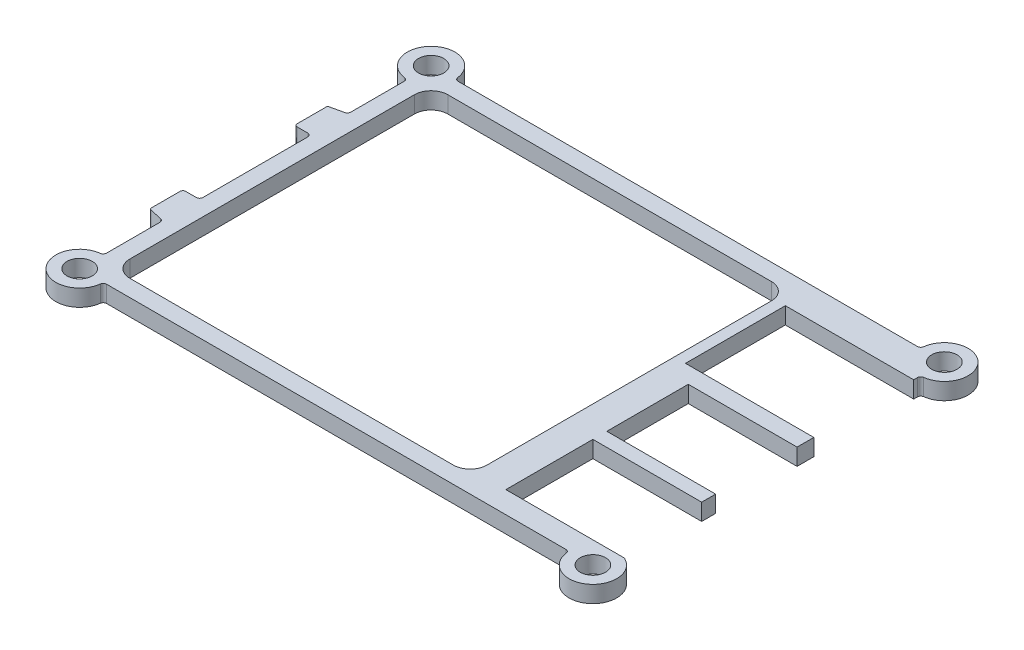
SolidWorks part; units mm, degrees
material "Balsa"
ref_plane "Front Plane" through (0, 0, 0) normal (0, 0, 1) x (1, 0, 0)
ref_plane "Top Plane" through (0, 0, 0) normal (0, 1, 0) x (1, 0, 0)
ref_plane "Right Plane" through (0, 0, 0) normal (1, 0, 0) x (0, 0, -1)
sketch "Sketch1" plane through (0, 0, 0) normal (0, 1, 0) x (1, 0, 0)
  line L0 (46, 0) -> (46, -63) construction
  line L5 (4.265, 0) -> (87.735, 0)
  line L6 (3.2, -3.25) -> (88.8, -3.25) construction
  line L7 (3.2, -3.25) -> (3.2, -59.75) construction
  line L8 (3.2, -59.75) -> (88.8, -59.75) construction
  line L9 (88.8, -3.25) -> (88.8, -59.75) construction
  line L10 (3.2, -3.25) -> (88.8, -59.75) construction
  line L11 (3.2, -59.75) -> (88.8, -3.25) construction
  line L12 (0, -4.265) -> (0, -58.735)
  line L14 (92, -4.265) -> (92, -58.735)
  line L15 (4.265, -63) -> (87.735, -63)
  circle A0 centre (0, 0) radius 2.265
  circle A1 centre (92, 0) radius 2.265
  circle A2 centre (92, -63) radius 2.265
  circle A3 centre (0, -63) radius 2.265
  arc A4 (4.265, 0) -> (0, -4.265) centre (0, 0) ccw
  arc A5 (92, -4.265) -> (87.735, 0) centre (92, 0) ccw
  arc A6 (87.735, -63) -> (92, -58.735) centre (92, -63) ccw
  arc A7 (0, -58.735) -> (4.265, -63) centre (0, -63) ccw
  point P7 (46, -31.5)
  dimension "D5" = 4.53
  dimension "D6" = 2
  dimension "D1" = 92
  dimension "D2" = 63
  dimension "D3" = 85.6
  dimension "D4" = 56.5
extrude "Boss-Extrude1" add sketch "Sketch1" along normal blind 3
sketch "Sketch2" plane through (0, 3, 0) normal (0, 1, 0) x (1, 0, 0)
  line L0 (0, -31.5) -> (92, -31.5) construction
  line L1 (0, -4.265) -> (0, -58.735) construction
  line L2 (92, -58.735) -> (92, -4.265) construction
  line L4 (0, -21.5) -> (6.5, -21.5)
  line L5 (0, -21.5) -> (0, -41.5)
  line L6 (0, -41.5) -> (6.5, -41.5)
  line L7 (6.5, -21.5) -> (6.5, -41.5)
  point P11 (0, -31.5)
  dimension "D1" = 20
  dimension "D2" = 6.5
extrude "Cut-Extrude1" cut sketch "Sketch2" against normal blind 3
sketch "Sketch3" plane through (0, 3, 0) normal (0, 1, 0) x (1, 0, 0)
  line L0 (-2.7, -15.5) -> (0, -14.9)
  line L1 (0, -21.5) -> (-2.5, -21.5)
  line L2 (0, -21.5) -> (0, -14.9)
  line L4 (-3, -21) -> (-3, -15.8)
  line L5 (6.5, -31.5) -> (-19.974, -31.5) construction
  line L6 (6.5, -41.5) -> (6.5, -21.5) construction
  line L7 (-3, -42) -> (-3, -47.2)
  line L8 (0, -41.5) -> (-2.5, -41.5)
  line L9 (0, -41.5) -> (0, -48.1)
  line L10 (-2.7, -47.5) -> (0, -48.1)
  arc A0 (-3, -21) -> (-2.5, -21.5) centre (-2.5, -21) ccw
  arc A1 (-3, -15.8) -> (-2.7, -15.5) centre (-2.7, -15.8) cw
  arc A2 (-3, -47.2) -> (-2.7, -47.5) centre (-2.7, -47.2) ccw
  arc A3 (-3, -42) -> (-2.5, -41.5) centre (-2.5, -42) cw
  point P7 (-3, -21.5)
  point P10 (-3, -15.5)
  dimension "D3" = 0.5
  dimension "D4" = 0.3
  dimension "D1" = 3
  dimension "D2" = 6
  dimension "D5" = 6.6
extrude "Boss-Extrude2" add sketch "Sketch3" against normal blind 3
sketch "Sketch4" plane through (0, 3, 0) normal (0, 1, 0) x (1, 0, 0)
  line L0 (0, -4.265) -> (0, -14.9) construction
  line L1 (6, -3) -> (64, -3)
  line L2 (3, -6) -> (3, -57)
  line L3 (6, -60) -> (64, -60)
  line L4 (67, -6) -> (67, -57)
  line L6 (4.265, -63) -> (87.735, -63) construction
  line L7 (87.735, 0) -> (4.265, 0) construction
  arc A0 (6, -60) -> (3, -57) centre (6, -57) cw
  arc A1 (67, -57) -> (64, -60) centre (64, -57) cw
  arc A2 (67, -6) -> (64, -3) centre (64, -6) ccw
  arc A3 (3, -6) -> (6, -3) centre (6, -6) cw
  dimension "D5" = 3
  dimension "D1" = 3
  dimension "D2" = 3
  dimension "D3" = 3
  dimension "D4" = 67
extrude "Cut-Extrude2" cut sketch "Sketch4" against normal blind 3
sketch "Sketch5" plane through (0, 3, 0) normal (0, 1, 0) x (1, 0, 0)
  line L0 (-2.5, -41.5) -> (3, -41.5) construction
  line L1 (3, -21.5) -> (0, -21.5)
  line L2 (3, -21.5) -> (3, -41.5)
  line L3 (3, -41.5) -> (0, -41.5)
  line L4 (0, -21.5) -> (0, -41.5)
extrude "Boss-Extrude3" add sketch "Sketch5" against normal blind 3
sketch "Sketch6" plane through (0, 3, 0) normal (0, 1, 0) x (1, 0, 0)
  line L0 (67, -57) -> (67, -6) construction
  line L1 (69, -5.5) -> (96.0101, -5.5)
  line L2 (69, -5.5) -> (69, -23.4)
  line L3 (69, -23.4) -> (96.0101, -23.4)
  line L4 (96.0101, -5.5) -> (96.0101, -23.4)
  line L5 (87.735, 0) -> (4.265, 0) construction
  dimension "D1" = 2
  dimension "D2" = 17.9
  dimension "D3" = 5.5
extrude "Cut-Extrude3" cut sketch "Sketch6" against normal blind 3
sketch "Sketch7" plane through (0, 3, 0) normal (0, 1, 0) x (1, 0, 0)
  line L0 (92, -58.735) -> (92, -23.4) construction
  line L1 (72.5, -26.4) -> (92, -26.4)
  line L2 (72.5, -26.4) -> (72.5, -41)
  line L3 (72.5, -41) -> (92, -41)
  line L4 (92, -26.4) -> (92, -41)
  line L5 (69, -23.4) -> (92, -23.4) construction
  line L6 (67, -57) -> (67, -6) construction
  line L7 (4.265, -63) -> (87.735, -63) construction
  dimension "D1" = 3
  dimension "D2" = 5.5
  dimension "D3" = 22
extrude "Cut-Extrude4" cut sketch "Sketch7" against normal blind 3
sketch "Sketch8" plane through (0, 3, 0) normal (0, 1, 0) x (1, 0, 0)
  line L0 (92, -58.735) -> (92, -41) construction
  line L1 (72.5, -43.5) -> (92, -43.5)
  line L2 (72.5, -43.5) -> (72.5, -59.1)
  line L3 (72.5, -59.1) -> (92, -59.1)
  line L4 (92, -43.5) -> (92, -59.1)
  line L5 (72.5, -41) -> (92, -41) construction
  line L6 (67, -57) -> (67, -6) construction
  line L7 (4.265, -63) -> (87.735, -63) construction
  dimension "D1" = 2.5
  dimension "D2" = 5.5
  dimension "D3" = 3.9
extrude "Cut-Extrude5" cut sketch "Sketch8" against normal blind 3
sketch "Sketch9" plane through (0, 3, 0) normal (0, 1, 0) x (1, 0, 0)
  line L1 (92, -59.1) -> (94.0196, -59.1)
  line L2 (92, -59.1) -> (92, -58.5257)
  line L3 (92, -58.5257) -> (94.0196, -58.5257)
  line L4 (94.0196, -59.1) -> (94.0196, -58.5257)
extrude "Cut-Extrude6" cut sketch "Sketch9" against normal blind 3
fillet "Fillet1" radius 0.6 12 edges at (87.735, 1.5, 0) (92, 1.5, 4.265) (93.7263, 1.5, 59.1) (87.735, 1.5, 63) (4.265, 1.5, 63) (0, 1.5, 58.735) (0, 1.5, 48.1) (0, 1.5, 41.5) (4.265, 1.5, 0) (0, 1.5, 14.9) (0, 1.5, 4.265) (0, 1.5, 21.5)
